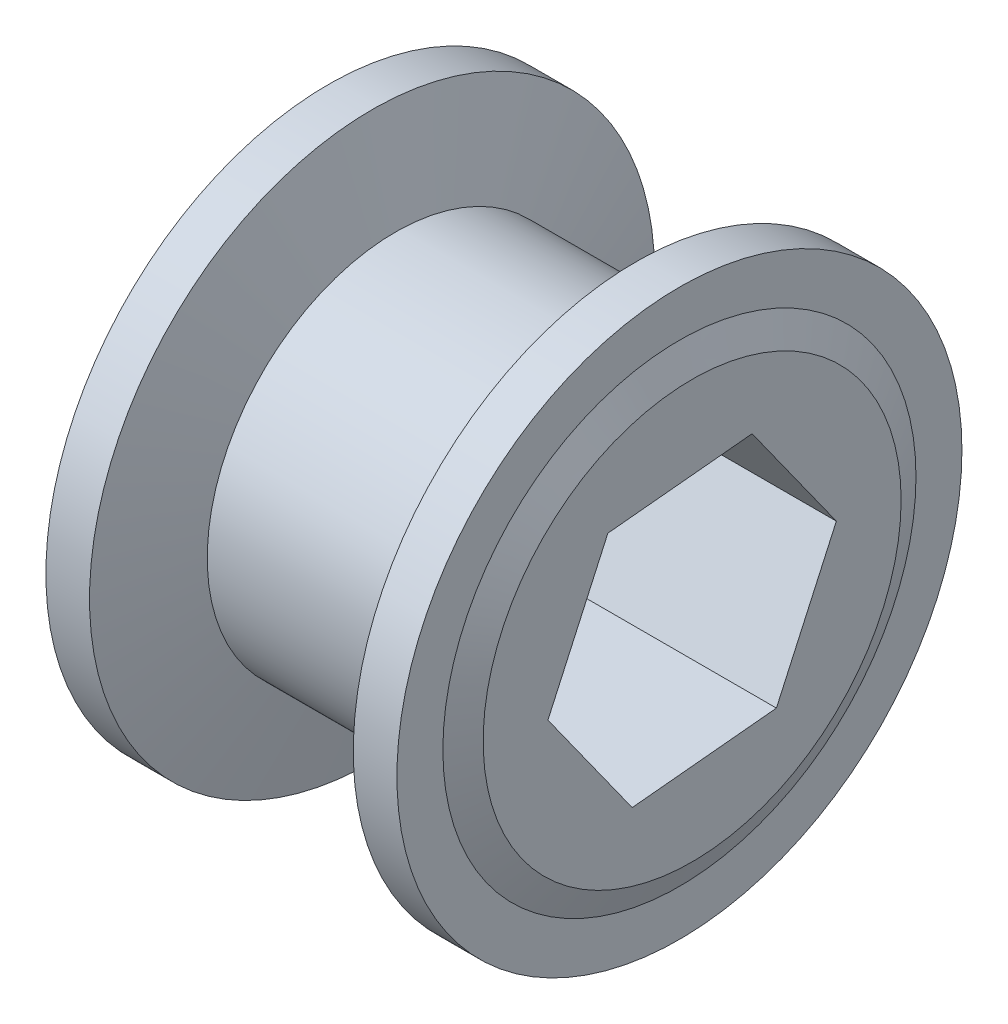
SolidWorks part; units mm, degrees
ref_plane "Front Plane" through (0, 0, 0) normal (0, 0, 1) x (1, 0, 0)
ref_plane "Top Plane" through (0, 0, 0) normal (0, 1, 0) x (1, 0, 0)
ref_plane "Right Plane" through (0, 0, 0) normal (1, 0, 0) x (0, 0, -1)
sketch "Sketch2" plane through (0, 0, 0) normal (0, 0, 1) x (1, 0, 0)
  line L0 (0, 0) -> (0, 9.525) construction
  line L1 (-5.4878, 9.525) -> (5.4878, 9.525)
  line L2 (5.4878, 9.525) -> (6.6734, 14.2965)
  line L3 (6.6734, 14.2965) -> (8.8818, 14.2965)
  line L4 (8.8818, 14.2965) -> (8.8818, 11.9707)
  line L5 (14.1607, 0) -> (-14.1607, 0)
  line L6 (8.8818, 11.9707) -> (9.525, 10.5754)
  line L7 (9.525, 10.5754) -> (9.525, 0)
  line L8 (9.525, 0) -> (14.1607, 0)
  line L9 (-9.525, 0) -> (-14.1607, 0)
  line L10 (-9.525, 10.5754) -> (-9.525, 0)
  line L11 (-8.8818, 11.9707) -> (-9.525, 10.5754)
  line L12 (-8.8818, 14.2965) -> (-8.8818, 11.9707)
  line L13 (-6.6734, 14.2965) -> (-8.8818, 14.2965)
  line L14 (-5.4878, 9.525) -> (-6.6734, 14.2965)
  point P17 (6.6854, 9.525)
  point P18 (9.1046, 15.0555)
  point P19 (10.5548, 15.0104)
  point P20 (0, 0)
  point P21 (12.9488, 10.5754)
  point P22 (6.6854, 14.6224)
  point P23 (7.8025, 14.312)
  point P24 (5.4878, 9.525)
  point P25 (8.8818, 14.2965)
  point P26 (0, 0)
  dimension "D1" = 15.24
  dimension "D2" = 9.525
  dimension "D3" = 19.05
revolve "Revolve1" add sketch "Sketch2" angle 360 about L5
sketch "Sketch3" plane through (9.525, 0, 0) normal (1, 0, 0) x (0, 0, -1)
  line L1 (4.2644, -5.9648) -> (7.2978, 0.7106)
  line L2 (7.2978, 0.7106) -> (3.0335, 6.6754)
  line L3 (3.0335, 6.6754) -> (-4.2644, 5.9648)
  line L4 (-4.2644, 5.9648) -> (-7.2978, -0.7106)
  line L5 (-7.2978, -0.7106) -> (-3.0335, -6.6754)
  line L6 (-3.0335, -6.6754) -> (4.2644, -5.9648)
  circle A0 centre (0, 0) radius 6.35 construction
  dimension "D1" = 12.7
extrude "Cut-Extrude1" cut sketch "Sketch3" against normal through all
